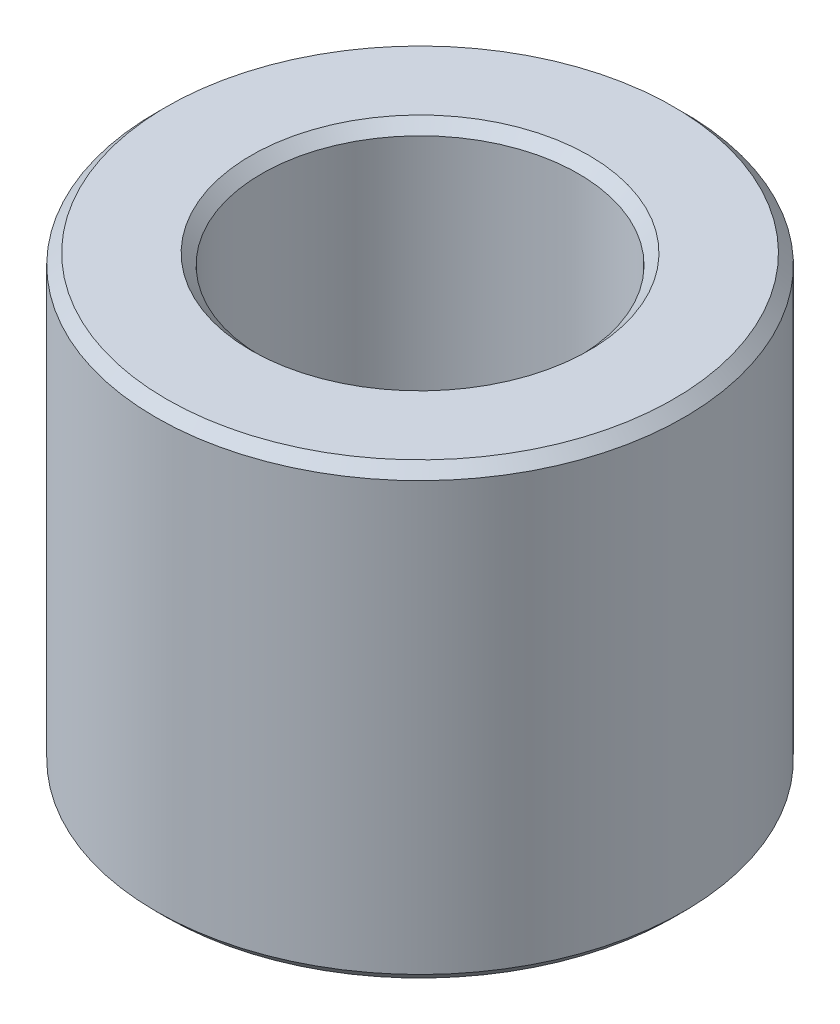
SolidWorks part; units mm, degrees
ref_plane "Front Plane" through (0, 0, 0) normal (0, 0, 1) x (1, 0, 0)
ref_plane "Top Plane" through (0, 0, 0) normal (0, 1, 0) x (1, 0, 0)
ref_plane "Right Plane" through (0, 0, 0) normal (1, 0, 0) x (0, 0, -1)
sketch "Sketch1" plane through (0, 0, 0) normal (0, 1, 0) x (1, 0, 0)
  circle A0 centre (0, 0) radius 3
  circle A1 centre (0, 0) radius 5
  dimension "D1" = 6
  dimension "D2" = 2
extrude "Boss-Extrude1" add sketch "Sketch1" along normal blind 8.5
chamfer "Chamfer1" distance 0.2 angle 45 4 edges at (0, 8.5, 3) (0, 8.5, 5) (0, 0, 3) (0, 0, 5)
